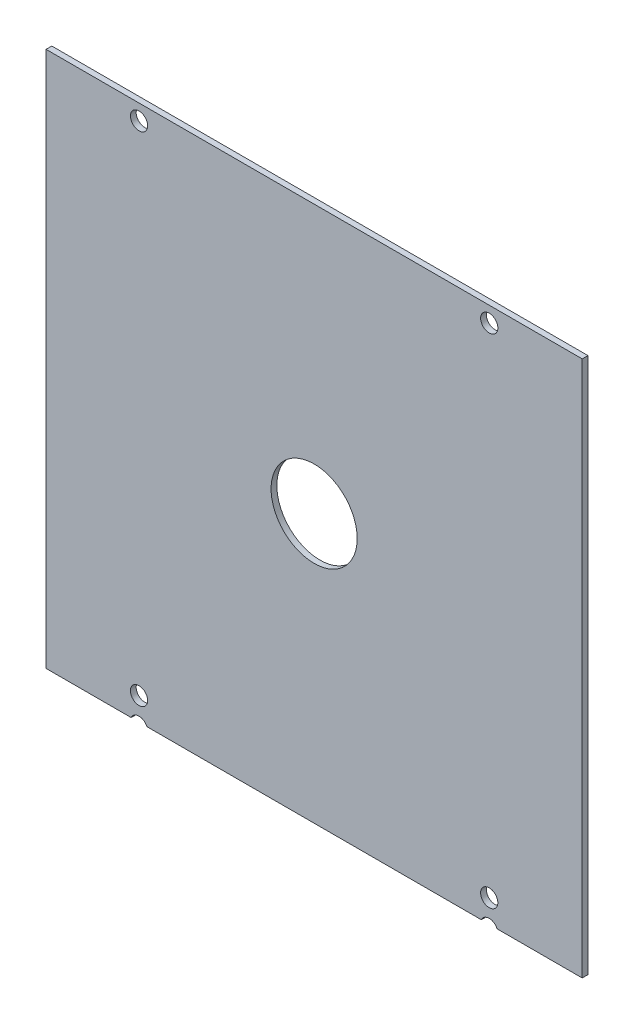
SolidWorks part; units mm, degrees
material "6061 Сплав"
ref_plane "Front Plane" through (0, 0, 0) normal (0, 0, 1) x (1, 0, 0)
ref_plane "Top Plane" through (0, 0, 0) normal (0, 1, 0) x (1, 0, 0)
ref_plane "Right Plane" through (0, 0, 0) normal (1, 0, 0) x (0, 0, -1)
sketch "Sketch1" plane through (0, 0, 0) normal (0, 0, 1) x (1, 0, 0)
  line L1 (46.7, -46.7) -> (-46.7, -46.7)
  line L2 (46.7, -46.7) -> (46.7, 46.7)
  line L3 (46.7, 46.7) -> (-46.7, 46.7)
  line L4 (-46.7, -46.7) -> (-46.7, 46.7)
  line L5 (46.7, -46.7) -> (-46.7, 46.7) construction
  line L6 (46.7, 46.7) -> (-46.7, -46.7) construction
  point P0 (0, 0)
  dimension "D1" = 93.4
  dimension "D2" = 93.4
extrude "Boss-Extrude1" add sketch "Sketch1" along normal blind 1
hole_wizard "Ø3.0 (3) Diameter Hole1" positions "Sketch3" profile "Sketch2" hole size "Ø3.0" standard "ANSI Metric"
sketch "Sketch3" plane through (0, 0, 1) normal (0, 0, 1) x (1, 0, 0)
  line L6 (-46.7, -46.7) -> (46.7, -46.7) construction
  line L9 (46.7, 46.7) -> (-46.7, 46.7) construction
  line L10 (0, 46.7) -> (0, 163.7587) construction
  line L11 (0, 46.7) -> (0, -152.1509) construction
  point P0 (-30.5, -47.3)
  point P2 (30.5, -47.3)
  point P15 (30.5, -42.7)
  point P17 (-30.5, -42.7)
  point P54 (-30.5, 44)
  point P56 (30.5, 44)
  point P58 (-30.5, -66)
  point P60 (30.5, -66)
  dimension "D2" = 4
  dimension "D3" = 2.7
  dimension "D4" = 4
  dimension "D5" = 30.5
  dimension "D6" = 30.5
  dimension "D7" = 94
  dimension "D8" = 30.5
  dimension "D9" = 2.7
  dimension "D10" = 94
  dimension "D11" = 30.5
  dimension "D12" = 30.5
  dimension "D13" = 30.5
  dimension "D14" = 30.5
  dimension "D15" = 30.5
  dimension "D16" = 112.7
  dimension "D17" = 112.7
sketch "Sketch2" plane through (-30.5, -47.3, 1) normal (1, 0, 0) x (0, -1, 0)
  line L0 (0, 0) -> (0, 1)
  line L1 (0, 1) -> (1.5, 1)
  line L2 (1.5, 1) -> (1.5, 0)
  line L5 (1.5, 0) -> (0, 0)
  line L10 (0, 1) -> (-1.5, 1) construction
  line L11 (0, -6.35) -> (0, 107.95) construction
  dimension "Hole Dia." = 3
  dimension "Hole Depth" = 1
  dimension "Drill Angle" = 180
sketch "Эскиз1" plane through (0, 0, 1) normal (0, 0, 1) x (1, 0, 0)
  circle A0 centre (0, 0) radius 7.5
extrude "Вырез-Вытянуть1" cut sketch "Эскиз1" against normal through all
